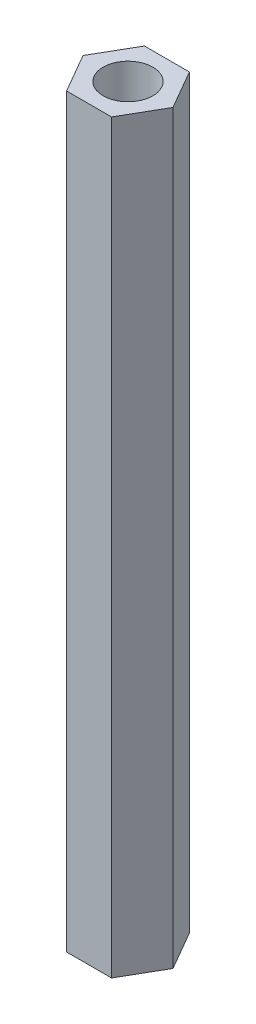
SolidWorks part; units mm, degrees
ref_plane "Front Plane" through (0, 0, 0) normal (0, 0, 1) x (1, 0, 0)
ref_plane "Top Plane" through (0, 0, 0) normal (0, 1, 0) x (1, 0, 0)
ref_plane "Right Plane" through (0, 0, 0) normal (1, 0, 0) x (0, 0, -1)
sketch "Sketch1" plane through (0, 0, 0) normal (0, 1, 0) x (1, 0, 0)
  line L1 (2.7135, 0) -> (1.3568, 2.35)
  line L2 (1.3568, 2.35) -> (-1.3568, 2.35)
  line L3 (-1.3568, 2.35) -> (-2.7135, 0)
  line L4 (-2.7135, 0) -> (-1.3568, -2.35)
  line L5 (-1.3568, -2.35) -> (1.3568, -2.35)
  line L6 (1.3568, -2.35) -> (2.7135, 0)
  circle A0 centre (0, 0) radius 2.35 construction
  circle A1 centre (0, 0) radius 1.5
  dimension "D1" = 4.7
extrude "Boss-Extrude1" add sketch "Sketch1" along normal blind 45
